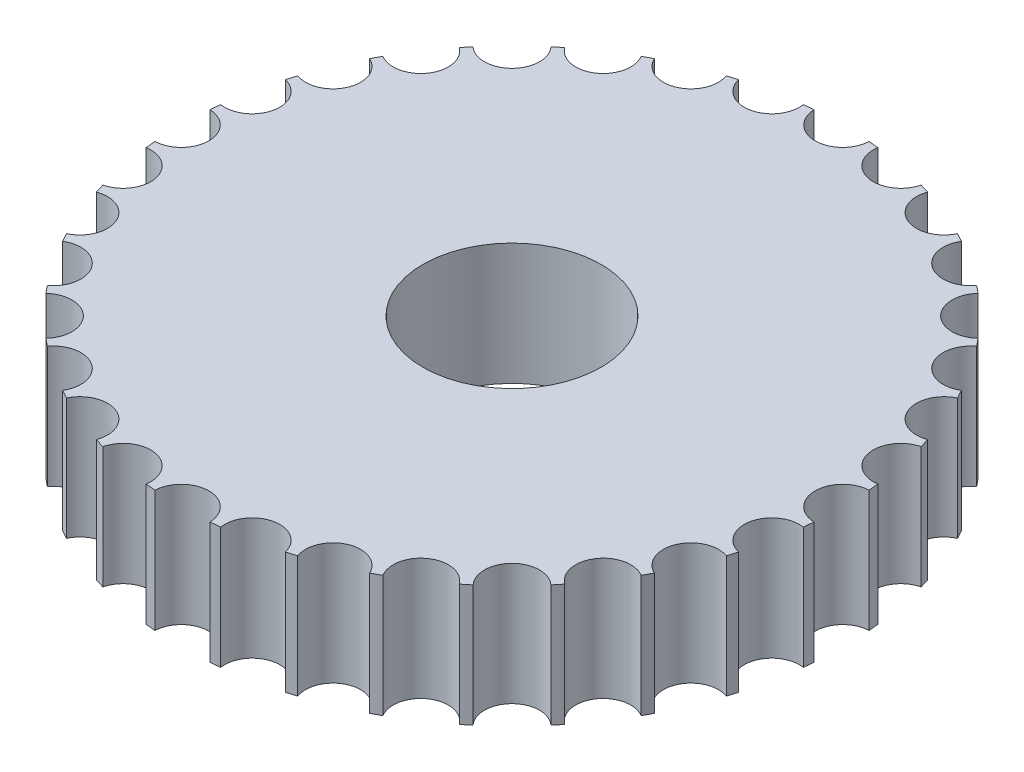
SolidWorks part; units mm, degrees
ref_plane "Front Plane" through (0, 0, 0) normal (0, 0, 1) x (1, 0, 0)
ref_plane "Top Plane" through (0, 0, 0) normal (0, 1, 0) x (1, 0, 0)
ref_plane "Right Plane" through (0, 0, 0) normal (1, 0, 0) x (0, 0, -1)
sketch "Sketch1" plane through (0, 0, 0) normal (0, 1, 0) x (1, 0, 0)
  line L0 (0, -55) -> (0, 55) construction
  circle A0 centre (0, 0) radius 40.8092
  arc A1 (-3.397, 40.6676) -> (3.397, 40.6676) centre (0, 40.8092) ccw
  arc A2 (4.6021, 40.5489) -> (11.2656, 39.2234) centre (7.9615, 40.0251) ccw
  arc A3 (12.4243, 38.8719) -> (18.7013, 36.2719) centre (15.617, 37.7028) ccw
  arc A4 (19.7691, 35.7011) -> (25.4182, 31.9265) centre (22.6724, 33.9316) ccw
  arc A5 (26.3542, 31.1584) -> (31.1584, 26.3542) centre (28.8565, 28.8565) ccw
  arc A6 (31.9265, 25.4182) -> (35.7011, 19.7691) centre (33.9316, 22.6724) ccw
  arc A7 (36.2719, 18.7013) -> (38.8719, 12.4243) centre (37.7028, 15.617) ccw
  arc A8 (39.2234, 11.2656) -> (40.5489, 4.6021) centre (40.0251, 7.9615) ccw
  arc A9 (40.6676, 3.397) -> (40.6676, -3.397) centre (40.8092, 0) ccw
  arc A10 (40.5489, -4.6021) -> (39.2234, -11.2656) centre (40.0251, -7.9615) ccw
  arc A11 (38.8719, -12.4243) -> (36.2719, -18.7013) centre (37.7028, -15.617) ccw
  arc A12 (35.7011, -19.7691) -> (31.9265, -25.4182) centre (33.9316, -22.6724) ccw
  arc A13 (31.1584, -26.3542) -> (26.3542, -31.1584) centre (28.8565, -28.8565) ccw
  arc A14 (25.4182, -31.9265) -> (19.7691, -35.7011) centre (22.6724, -33.9316) ccw
  arc A15 (18.7013, -36.2719) -> (12.4243, -38.8719) centre (15.617, -37.7028) ccw
  arc A16 (11.2656, -39.2234) -> (4.6021, -40.5489) centre (7.9615, -40.0251) ccw
  arc A17 (3.397, -40.6676) -> (-3.397, -40.6676) centre (0, -40.8092) ccw
  arc A18 (-4.6021, -40.5489) -> (-11.2656, -39.2234) centre (-7.9615, -40.0251) ccw
  arc A19 (-12.4243, -38.8719) -> (-18.7013, -36.2719) centre (-15.617, -37.7028) ccw
  arc A20 (-19.7691, -35.7011) -> (-25.4182, -31.9265) centre (-22.6724, -33.9316) ccw
  arc A21 (-26.3542, -31.1584) -> (-31.1584, -26.3542) centre (-28.8565, -28.8565) ccw
  arc A22 (-31.9265, -25.4182) -> (-35.7011, -19.7691) centre (-33.9316, -22.6724) ccw
  arc A23 (-36.2719, -18.7013) -> (-38.8719, -12.4243) centre (-37.7028, -15.617) ccw
  arc A24 (-39.2234, -11.2656) -> (-40.5489, -4.6021) centre (-40.0251, -7.9615) ccw
  arc A25 (-40.6676, -3.397) -> (-40.6676, 3.397) centre (-40.8092, 0) ccw
  arc A26 (-40.5489, 4.6021) -> (-39.2234, 11.2656) centre (-40.0251, 7.9615) ccw
  arc A27 (-38.8719, 12.4243) -> (-36.2719, 18.7013) centre (-37.7028, 15.617) ccw
  arc A28 (-35.7011, 19.7691) -> (-31.9265, 25.4182) centre (-33.9316, 22.6724) ccw
  arc A29 (-31.1584, 26.3542) -> (-26.3542, 31.1584) centre (-28.8565, 28.8565) ccw
  arc A30 (-25.4182, 31.9265) -> (-19.7691, 35.7011) centre (-22.6724, 33.9316) ccw
  arc A31 (-18.7013, 36.2719) -> (-12.4243, 38.8719) centre (-15.617, 37.7028) ccw
  arc A32 (-11.2656, 39.2234) -> (-4.6021, 40.5489) centre (-7.9615, 40.0251) ccw
  circle A33 centre (0, 0) radius 11
  point P10 (0, 37.4092)
  point P99 (0, 0)
  dimension "D1" = 3.4
  dimension "D2" = 32
  dimension "D4" = 22
  dimension "D3" = 8
extrude "Boss-Extrude1" add sketch "Sketch1" along normal blind 15 contours A32 A0 A31 A30 A29 A28 A27 A26 A25 A24 A23 A22 A21 A20 A19 A18 A17 A16 A15 A14 A13 A12 A11 A10 A9 A8 A7
